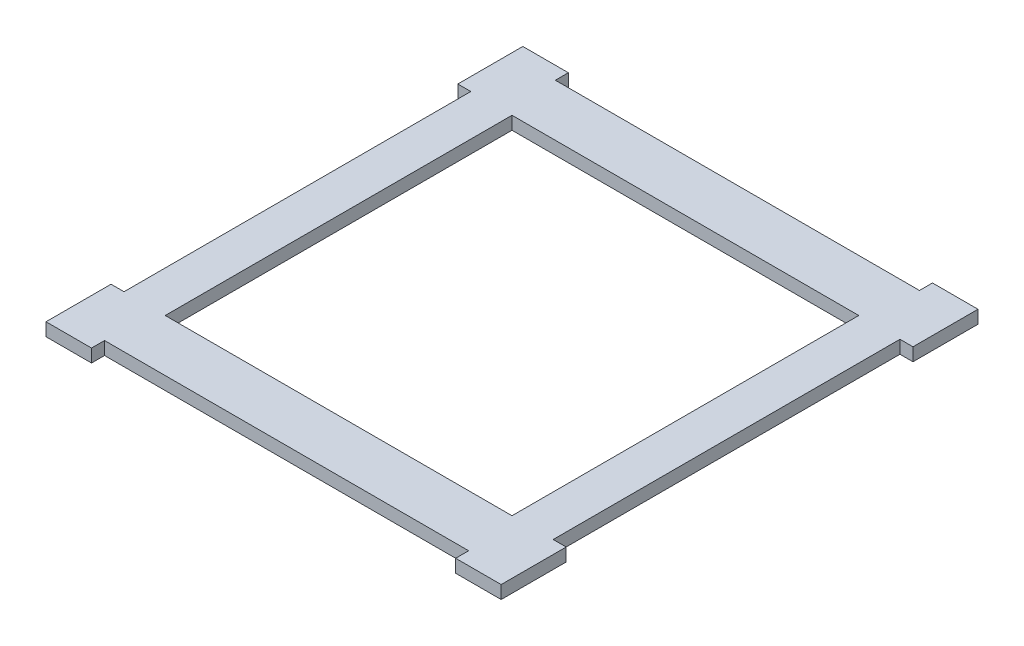
SolidWorks part; units mm, degrees
ref_plane "Front" through (0, 0, 0) normal (0, 0, 1) x (1, 0, 0)
ref_plane "Top" through (0, 0, 0) normal (0, 1, 0) x (1, 0, 0)
ref_plane "Right" through (0, 0, 0) normal (1, 0, 0) x (0, 0, -1)
sketch "Sketch2" plane through (0, 0, 0) normal (0, 1, 0) x (1, 0, 0)
  line L1 (-54.5, 52) -> (54.5, 52)
  line L2 (-54.5, 52) -> (-54.5, -52)
  line L3 (-54.5, -52) -> (54.5, -52)
  line L4 (54.5, 52) -> (54.5, -52)
  line L5 (-54.5, 52) -> (54.5, -52) construction
  line L6 (-54.5, -52) -> (54.5, 52) construction
  line L7 (-40, 40) -> (40, 40)
  line L8 (-40, 40) -> (-40, -40)
  line L9 (-40, -40) -> (40, -40)
  line L10 (40, 40) -> (40, -40)
  line L11 (-40, 40) -> (40, -40) construction
  line L12 (-40, -40) -> (40, 40) construction
  point P0 (0, 0)
  point P6 (0, 0)
  dimension "D1" = 104
  dimension "D2" = 109
  dimension "D3" = 80
  dimension "D4" = 80
extrude "Boss-Extrude2" add sketch "Sketch2" along normal blind 3
sketch "Sketch3" plane through (0, 0, -52) normal (0, 0, -1) x (-1, 0, 0)
  line L0 (54.5, 3) -> (42, 3)
  line L1 (-54.5, 3) -> (54.5, 3) construction
  line L2 (42, 3) -> (42, 0)
  line L3 (-54.5, 0) -> (54.5, 0) construction
  line L4 (42, 0) -> (54.5, 0)
  line L5 (54.5, 0) -> (54.5, 3)
  dimension "D1" = 12.5
extrude "Boss-Extrude3" add sketch "Sketch3" along normal blind 5
mirror "Mirror1" about plane through (0, 0, 0) normal (0, 0, 1) of bodies 103
mirror "Mirror2" about plane through (0, 0, 0) normal (1, 0, 0) of bodies 104
sketch "Sketch4" plane through (0, 0, 0) normal (0, -1, 0) x (1, 0, 0)
  line L0 (-49.5, -40) -> (-54.5, -40)
  line L1 (-54.5, -57) -> (-54.5, 57) construction
  line L2 (-54.5, -40) -> (-49.5, -40)
  line L3 (-49.5, 40) -> (-54.5, 40)
  line L4 (-54.5, 40) -> (-49.5, 40)
  line L5 (-49.5, 40) -> (-49.5, -40)
  line L6 (-54.5, -40) -> (-54.5, 40)
  line M6 (-54.5, 57) -> (-54.5, -57)
  dimension "D1" = 5
  dimension "D2" = 5
extrude "Cut-Extrude1" cut sketch "Sketch4" against normal blind 5 contours L5 L3 L0 M6
mirror "Mirror3" about plane through (0, 0, 0) normal (1, 0, 0) of "Cut-Extrude1"
sketch "Sketch5" plane through (0, 0, 0) normal (0, -1, 0) x (1, 0, 0)
  line L0 (54.5, -40) -> (52.5, -40)
  line L1 (49.5, -40) -> (54.5, -40) construction
  line L2 (52.5, -40) -> (52.5, -57)
  line L3 (42, -57) -> (54.5, -57) construction
  line L4 (52.5, -57) -> (52.5, -55)
  line L5 (52.5, -55) -> (42, -55)
  line L6 (42, -57) -> (42, -52) construction
  line L7 (54.5, -40) -> (54.5, -57)
  line L8 (54.5, -57) -> (42, -57)
  line L9 (42, -57) -> (42, -55)
  line M21 (42, -52) -> (42, -57)
  line M22 (42, -57) -> (54.5, -57)
  line M23 (54.5, -57) -> (54.5, -40)
  line M24 (54.5, -40) -> (49.5, -40)
  dimension "D1" = 2
  dimension "D2" = 2
extrude "Cut-Extrude2" cut sketch "Sketch5" against normal blind 10 contours L2 L5 M21 M22 | L2 M24 M22 M23
mirror "Mirror4" about plane through (0, 0, 0) normal (1, 0, 0) of "Cut-Extrude2"
mirror "Mirror5" about plane through (0, 0, 0) normal (0, 0, 1) of "Mirror4", "Cut-Extrude2"
